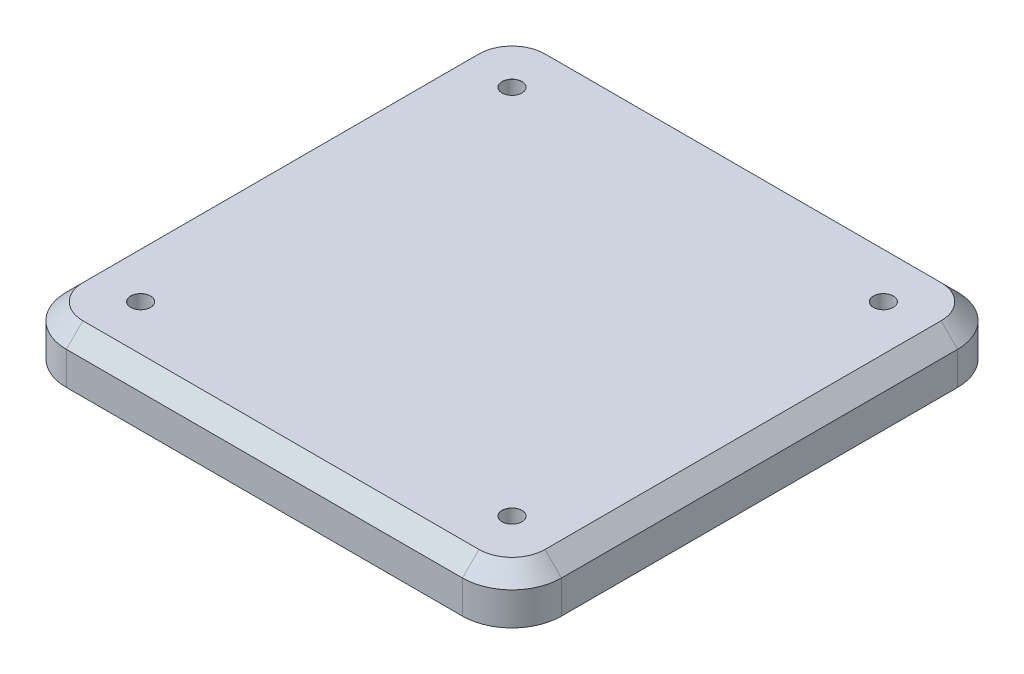
SolidWorks part; units mm, degrees
ref_plane "Front Plane" through (0, 0, 0) normal (0, 0, 1) x (1, 0, 0)
ref_plane "Top Plane" through (0, 0, 0) normal (0, 1, 0) x (1, 0, 0)
ref_plane "Right Plane" through (0, 0, 0) normal (1, 0, 0) x (0, 0, -1)
sketch "Sketch1" plane through (0, 0, 0) normal (0, 1, 0) x (1, 0, 0)
  line L1 (-150, 150) -> (150, 150)
  line L2 (-150, 150) -> (-150, -150)
  line L3 (-150, -150) -> (150, -150)
  line L4 (150, 150) -> (150, -150)
  line L5 (-150, 150) -> (150, -150) construction
  line L6 (-150, -150) -> (150, 150) construction
  point P0 (0, 0)
  dimension "D1" = 300
extrude "Boss-Extrude1" add sketch "Sketch1" along normal blind 30
sketch "Sketch2" plane through (0, 30, 0) normal (0, 1, 0) x (1, 0, 0)
  line L0 (0, 150) -> (0, -150) construction
  line L3 (-150, 0) -> (150, 0) construction
  line L4 (-150, 150) -> (-150, -150) construction
  line L5 (150, -150) -> (150, 150) construction
  line L6 (150, 150) -> (-150, 150) construction
  line L7 (-150, -150) -> (150, -150) construction
  line L9 (-112.5, 112.5) -> (112.5, 112.5) construction
  line L10 (-112.5, 112.5) -> (-112.5, -112.5) construction
  line L11 (-112.5, -112.5) -> (112.5, -112.5) construction
  line L12 (112.5, 112.5) -> (112.5, -112.5) construction
  line L13 (-112.5, 112.5) -> (112.5, -112.5) construction
  line L14 (-112.5, -112.5) -> (112.5, 112.5) construction
  point P6 (0, 0)
  point P18 (0, 0)
  point P19 (0, 0)
  point P20 (0, 0)
  point P21 (0, 0)
  point P22 (0, 0)
  dimension "D1" = 225
hole_wizard "Ø12.0mm Dowel Hole2" positions "Sketch7" profile "Sketch8" hole size "Ø12.0" standard "ANSI Metric"
sketch "Sketch7" plane through (0, 30, 0) normal (0, 1, 0) x (1, 0, 0)
  point P0 (-112.5, 112.5)
  point P3 (112.5, 112.5)
  point P6 (112.5, -112.5)
  point P9 (-112.5, -112.5)
sketch "Sketch8" plane through (-112.5, 30, -112.5) normal (1, 0, 0) x (0, 0, 1)
  line L0 (0, 0) -> (0, 13.6052)
  line L1 (0, 13.6052) -> (6, 10)
  line L2 (6, 10) -> (6, 0.025)
  line L3 (6, 0.025) -> (6.025, 0)
  line L5 (6.025, 0) -> (0, 0)
  line L6 (-6, 0.025) -> (-6.025, 0) construction
  line L10 (0, 13.6052) -> (-6, 10) construction
  line L11 (0, -6.35) -> (0, 107.95) construction
  dimension "Hole Dia." = 12
  dimension "Hole Depth" = 10
  dimension "Near C'Sink Dia." = 12.05
  dimension "Near C'Sink Angle" = 90
  dimension "Drill Angle" = 118
sketch "Sketch9" plane through (0, 0, 0) normal (0, -1, 0) x (-1, 0, 0)
  line L0 (0, -150) -> (0, 150) construction
  line L1 (150, -150) -> (-150, -150) construction
  line L2 (-150, 150) -> (150, 150) construction
  line L3 (150, 0) -> (-150, 0) construction
  line L4 (150, 150) -> (150, -150) construction
  line L5 (-150, -150) -> (-150, 150) construction
  line L7 (125, -125) -> (-125, -125) construction
  line L8 (125, -125) -> (125, 125) construction
  line L9 (125, 125) -> (-125, 125) construction
  line L10 (-125, -125) -> (-125, 125) construction
  line L11 (125, -125) -> (-125, 125) construction
  line L12 (125, 125) -> (-125, -125) construction
  point P12 (0, 0)
  dimension "D1" = 250
hole_wizard "Ø12.0mm Dowel Hole3" positions "Sketch10" profile "Sketch11" hole size "Ø12.0" standard "ANSI Metric"
sketch "Sketch10" plane through (0, 0, 0) normal (0, -1, 0) x (-1, 0, 0)
  point P0 (-125, 125)
  point P3 (125, 125)
  point P6 (125, -125)
  point P9 (-125, -125)
sketch "Sketch11" plane through (125, 0, -125) normal (1, 0, 0) x (0, 0, -1)
  line L0 (0, 0) -> (0, 13.6052)
  line L1 (0, 13.6052) -> (6, 10)
  line L2 (6, 10) -> (6, 0.025)
  line L3 (6, 0.025) -> (6.025, 0)
  line L5 (6.025, 0) -> (0, 0)
  line L6 (-6, 0.025) -> (-6.025, 0) construction
  line L10 (0, 13.6052) -> (-6, 10) construction
  line L11 (0, -6.35) -> (0, 107.95) construction
  dimension "Hole Dia." = 12
  dimension "Hole Depth" = 10
  dimension "Near C'Sink Dia." = 12.05
  dimension "Near C'Sink Angle" = 90
  dimension "Drill Angle" = 118
fillet "Fillet1" radius 30 4 edges at (150, 15, 150) (-150, 15, -150) (150, 15, -150) (-150, 15, 150)
chamfer "Chamfer1" distance 10 angle 45 8 edges at (-141.2132, 30, 141.2132) (-150, 30, 0) (-141.2132, 30, -141.2132) (0, 30, -150) (141.2132, 30, -141.2132) (150, 30, 0) (141.2132, 30, 141.2132) (0, 30, 150)
